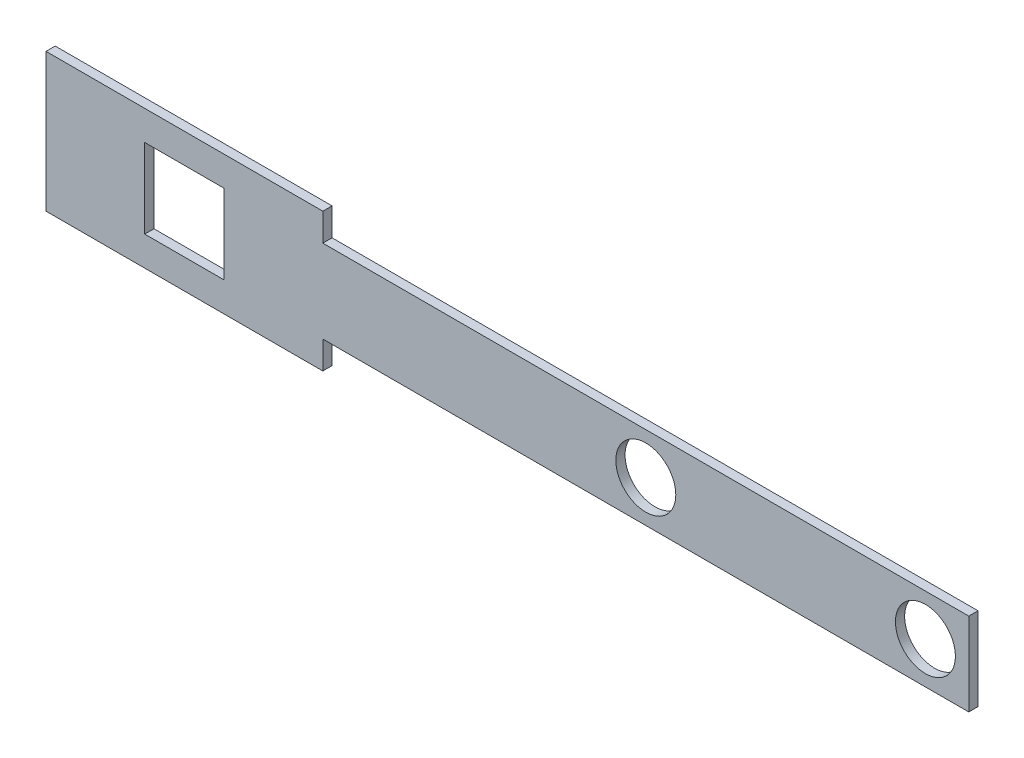
SolidWorks part; units mm, degrees
ref_plane "Front Plane" through (0, 0, 0) normal (0, 0, 1) x (1, 0, 0)
ref_plane "Top Plane" through (0, 0, 0) normal (0, 1, 0) x (1, 0, 0)
ref_plane "Right Plane" through (0, 0, 0) normal (1, 0, 0) x (0, 0, -1)
sketch "Sketch1" plane through (0, 0, 0) normal (0, 0, 1) x (1, 0, 0)
  line L0 (30, -3) -> (30, 0)
  line L1 (0, 0) -> (30, 0)
  line L2 (0, 0) -> (0, -15)
  line L3 (0, -15) -> (30, -15)
  line L5 (30, -3) -> (100, -3)
  line L6 (30, -12) -> (30, -15)
  line L7 (30, -12) -> (100, -12)
  line L8 (100, -3) -> (100, -12)
  dimension "D1" = 30
  dimension "D2" = 15
  dimension "D3" = 3
  dimension "D4" = 3
  dimension "D5" = 70
extrude "Boss-Extrude1" add sketch "Sketch1" along normal blind 1
sketch "Sketch3" plane through (0, 0, 0) normal (0, 0, -1) x (-1, 0, 0)
  line L0 (-30, -3) -> (-30, 0) construction
  line L3 (-19.3, -3.2) -> (-10.7, -3.2)
  line L4 (-19.3, -3.2) -> (-19.3, -11.8)
  line L5 (-19.3, -11.8) -> (-10.7, -11.8)
  line L6 (-10.7, -3.2) -> (-10.7, -11.8)
  line L7 (0, 0) -> (-30, 0) construction
  dimension "D1" = 8.6
  dimension "D3" = 10.7
  dimension "D2" = 8.6
  dimension "D4" = 3.2
extrude "Cut-Extrude2" cut sketch "Sketch3" against normal through all contours L3 L6 L5 L4
sketch "Sketch5" plane through (0, 0, 1) normal (0, 0, 1) x (1, 0, 0)
  line L1 (30, -3) -> (100, -3) construction
  circle A0 centre (65, -7.5) radius 3.25
  circle A1 centre (95.3, -7.5) radius 3.25
  dimension "D1" = 6.5
  dimension "D2" = 35
  dimension "D3" = 4.5
  dimension "D4" = 2
extrude "Cut-Extrude3" cut sketch "Sketch5" against normal through all both and the other way through all
